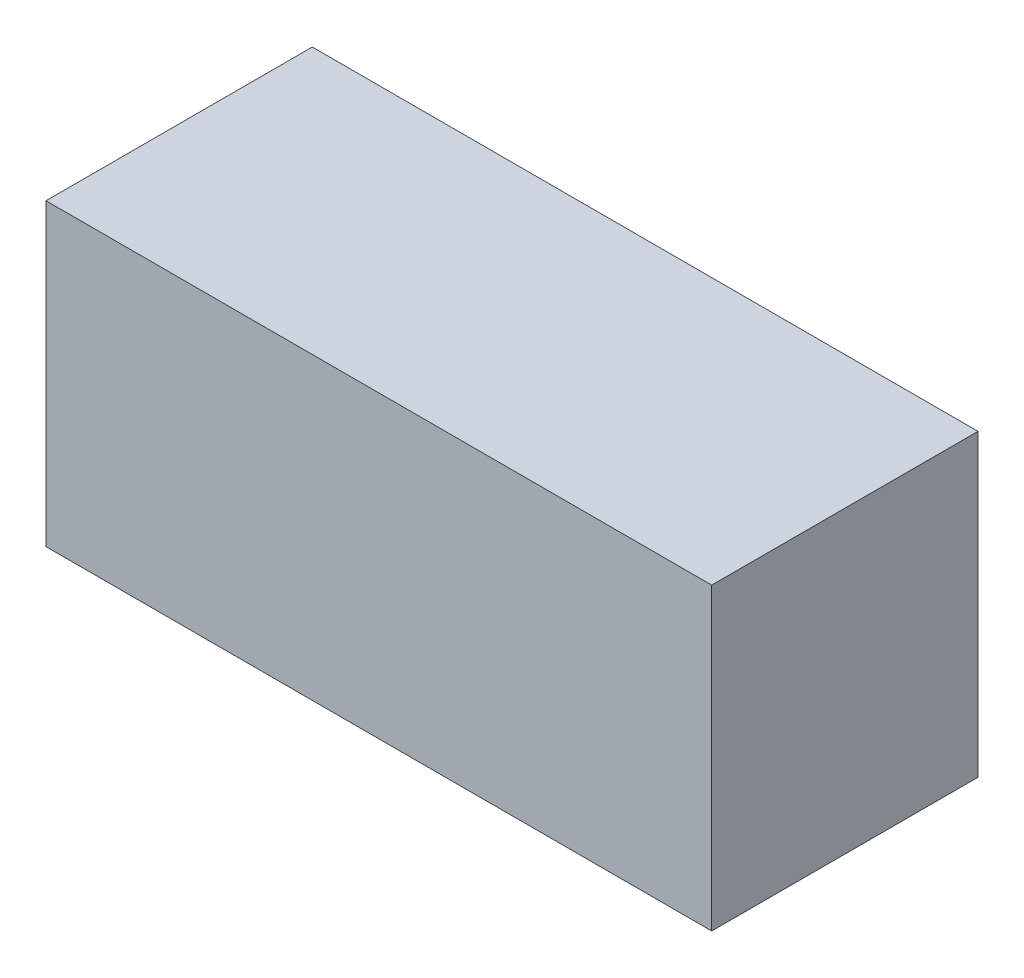
SolidWorks part; units mm, degrees
ref_plane "Front Plane" through (0, 0, 0) normal (0, 0, 1) x (1, 0, 0)
ref_plane "Top Plane" through (0, 0, 0) normal (0, 1, 0) x (1, 0, 0)
ref_plane "Right Plane" through (0, 0, 0) normal (1, 0, 0) x (0, 0, -1)
sketch "Sketch2" plane through (0, 0, 0) normal (0, 1, 0) x (1, 0, 0)
  line L1 (0, 0) -> (100, 0)
  line L2 (0, 0) -> (0, 40)
  line L3 (0, 40) -> (100, 40)
  line L4 (100, 0) -> (100, 40)
  dimension "D1" = 40
  dimension "D2" = 100
extrude "Boss-Extrude2" add sketch "Sketch2" along normal blind 45
